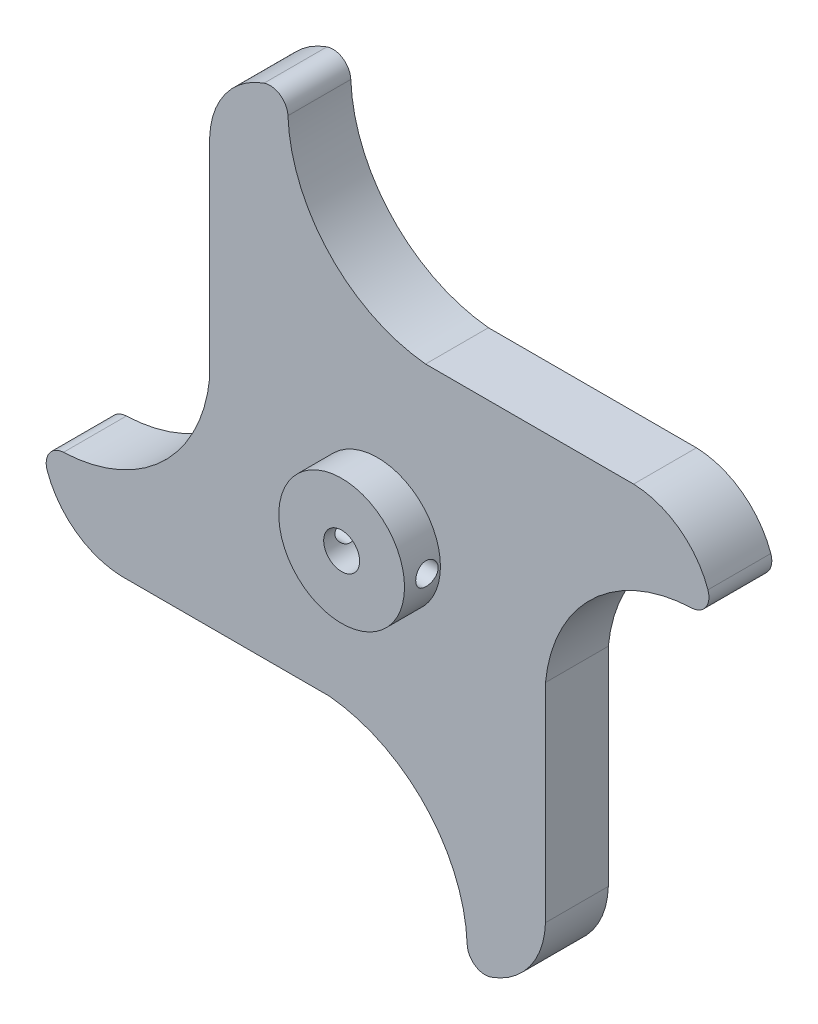
SolidWorks part; units mm, degrees
ref_plane "前视基准面" through (0, 0, 0) normal (0, 0, 1) x (1, 0, 0)
ref_plane "上视基准面" through (0, 0, 0) normal (0, 1, 0) x (1, 0, 0)
ref_plane "右视基准面" through (0, 0, 0) normal (1, 0, 0) x (0, 0, -1)
sketch "草图1" plane through (0, 0, 0) normal (0, 0, 1) x (1, 0, 0)
  circle A0 centre (0, 0) radius 2
  arc A5 (40.8798, 28.7896) -> (28.7896, 40.8798) centre (0, 0) ccw
  arc A7 (-28.7896, 40.8798) -> (-40.8798, 28.7896) centre (0, 0) ccw
  arc A9 (-40.8798, -28.7896) -> (-28.7896, -40.8798) centre (0, 0) ccw
  arc A11 (28.7896, -40.8798) -> (40.8798, -28.7896) centre (0, 0) ccw
  arc A13 (-22.8945, 32.8) -> (22.8945, 32.8) centre (0, 55.6945) ccw
  arc A14 (32.8, 22.8945) -> (32.8, -22.8945) centre (55.6945, 0) ccw
  arc A15 (22.8945, -32.8) -> (-22.8945, -32.8) centre (0, -55.6945) ccw
  arc A16 (-32.8, -22.8945) -> (-32.8, 22.8945) centre (-55.6945, 0) ccw
  arc A21 (-28.7896, 40.8798) -> (28.7896, 40.8798) centre (0, 55.6945) ccw
  arc A22 (40.8798, 28.7896) -> (40.8798, -28.7896) centre (55.6945, 0) ccw
  arc A23 (28.7896, -40.8798) -> (-28.7896, -40.8798) centre (0, -55.6945) ccw
  arc A24 (-40.8798, -28.7896) -> (-40.8798, 28.7896) centre (-55.6945, 0) ccw
  point P13 (45, 0)
  point P16 (0, 0)
  point P45 (0, 0)
  point P47 (0, 0)
  point P63 (0, 0)
  dimension "D1" = 4
  dimension "D3" = 4
  dimension "D4" = 4
extrude "凸台-拉伸1" add sketch "草图1" along normal blind 7 contours A24 A16 A9 A23 A15 A11 A22 A14 A5 A21 A13 A7 A0
sketch "草图2" plane through (0, 0, 7) normal (0, 0, 1) x (1, 0, 0)
  line L0 (24.2343, 0) -> (24.2343, 20.8516)
  line L1 (0, -24.2343) -> (-200, -24.2343)
  line L2 (-200, -71.6) -> (3.2733, -71.6)
  line L3 (0, -70) -> (-200, -70)
  line L4 (-200, -23.4) -> (-200, -71.6)
  line L5 (24.2343, 34.0432) -> (24.2343, 20.8516)
  line L6 (-200, -47.5) -> (-20.9464, -47.5)
  line L7 (-200, -23.4) -> (-42.5285, -23.4)
  line L8 (70, 0) -> (70, 107.3223)
  line L9 (24.2343, 34.0432) -> (24.2343, 107.3223)
  line L10 (-35.8334, -17.6395) -> (24.2343, 34.0432)
  line L11 (24.2343, 34.0432) -> (-43.4982, -24.2343)
  line L12 (0, -24.2343) -> (0, 0)
  line L13 (0, 0) -> (0, -24.2343)
  line L14 (-43.4982, -24.2343) -> (-43.4982, -70)
  line L15 (-310.8913, -229.5208) -> (-198.8913, -229.5208)
  line L16 (-254.8913, -229.5208) -> (-251.3913, -229.5208)
  line L17 (-251.3913, -229.5208) -> (-258.3913, -229.5208)
  line L18 (-258.3913, -229.5208) -> (-258.3913, -112.5315)
  line L19 (-258.3913, -112.5315) -> (-251.3913, -112.5315)
  line L20 (-251.3913, -112.5315) -> (-251.3913, -229.5208)
  line L21 (24.2343, 107.3223) -> (70, 107.3223)
  line L22 (47.1172, 107.3223) -> (47.1172, -141.393)
  line L23 (-20.9464, -47.5) -> (114.3656, -47.5)
  line L24 (0, 0) -> (0, -24.2343)
  circle A0 centre (0, -49) radius 21
  circle A1 centre (-310.8913, -229.5208) radius 38.25
  arc A2 (0, -24.2343) -> (24.2343, 0) centre (0, 0) ccw
  arc A3 (0, -70) -> (70, 0) centre (0, 0) ccw
  circle A4 centre (-198.8913, -229.5208) radius 38.25
  circle A5 centre (0, 0) radius 47.1172
  circle A10 centre (-254.8913, -208.9571) radius 21.4063
  point P19 (0, 0)
sketch "草图5" plane through (0, 0, 7) normal (0, 0, 1) x (1, 0, 0)
  line L1 (0, 2.5) -> (-1.7806, 2.5)
  line L2 (-1.7806, 2.5) -> (1.6583, 2.5)
  arc A0 (1.6583, 2.5) -> (-1.6583, 2.5) centre (0, 0) ccw
  circle A1 centre (0, 0) radius 7
extrude "凸台-拉伸2" add sketch "草图5" along normal blind 4
sketch "草图11" plane through (0, 0, 0) normal (1, 0, 0) x (0, 0, -1)
  line L0 (0, 0) -> (-7, 0)
  line L1 (-7, 0) -> (-10, 0)
  circle A0 centre (-8.5, 0) radius 1.25
extrude "切除-拉伸5" cut sketch "草图11" against normal blind 15 and the other way blind 8 contours L1 A0 | L1 A0
sketch "草图13" plane through (0, 0, 0) normal (0, 0, -1) x (-1, 0, 0)
  arc A0 (-25.2436, 31.0284) -> (25.2436, 31.0284) centre (0, 50.6945) ccw
  arc A1 (31.0284, 25.2436) -> (31.0284, -25.2436) centre (50.6945, 0) ccw
  arc A2 (25.2436, -31.0284) -> (-25.2436, -31.0284) centre (0, -50.6945) ccw
  arc A3 (-31.0284, -25.2436) -> (-31.0284, 25.2436) centre (-50.6945, 0) ccw
  arc A4 (-25.2436, 31.0284) -> (-31.0284, 25.2436) centre (0, 0) ccw
  circle A5 centre (0, 0) radius 82.6945
  arc A6 (-31.0284, -25.2436) -> (-25.2436, -31.0284) centre (0, 0) ccw
  arc A7 (25.2436, -31.0284) -> (31.0284, -25.2436) centre (0, 0) ccw
  arc A8 (31.0284, 25.2436) -> (25.2436, 31.0284) centre (0, 0) ccw
  point P14 (0, 0)
  dimension "D1" = 4
extrude "切除-拉伸13" cut sketch "草图13" against normal blind 10
fillet "圆角1" radius 2 4 edges at (-31.0284, -25.2436, 3.5) (31.0284, -25.2436, 3.5) (25.2436, 31.0284, 3.5) (-31.0284, 25.2436, 3.5)
fillet "圆角2" radius 2 4 edges at (-25.2436, -31.0284, 3.5) (25.2436, -31.0284, 3.5) (31.0284, 25.2436, 3.5) (-25.2436, 31.0284, 3.5)
sketch "草图14" plane through (0, 0, 0) normal (0, 0, -1) x (-1, 0, 0)
  line L0 (0, 18.6945) -> (-34.0956, 18.6945)
  line L1 (18.6945, 0) -> (18.6945, 34.0956)
  line L2 (0, -18.6945) -> (34.0956, -18.6945)
  line L3 (-18.6945, 0) -> (-18.6945, -34.0956)
  line L4 (34.0956, -16.9082) -> (34.0956, -18.6945)
  line L5 (-16.9082, -34.0956) -> (-18.6945, -34.0956)
  line L6 (-34.0956, 16.9082) -> (-34.0956, 18.6945)
  line L7 (16.9082, 34.0956) -> (18.6945, 34.0956)
  line L8 (13.8017, 34.0956) -> (18.6945, 34.0956)
  line L9 (34.0956, -13.8017) -> (34.0956, -18.6945)
  line L10 (-13.8017, -34.0956) -> (-18.6945, -34.0956)
  line L11 (-34.0956, 13.8017) -> (-34.0956, 18.6945)
  arc A1 (-23.9852, 29.5117) -> (23.9852, 29.5117) centre (0, 50.6945) ccw construction
  arc A5 (0, 18.6945) -> (13.8017, 34.0956) centre (-0.7997, 33.296) ccw
  arc A6 (18.6945, 0) -> (34.0956, -13.8017) centre (33.296, 0.7997) ccw
  arc A7 (0, -18.6945) -> (-13.8017, -34.0956) centre (0.7997, -33.296) ccw
  arc A8 (-18.6945, 0) -> (-34.0956, 13.8017) centre (-33.296, -0.7997) ccw
  point P22 (0, 0)
  point P29 (0, 0)
  point P35 (0, 0)
  point P41 (0, 0)
  dimension "D1" = 4
  dimension "D3" = 4
  dimension "D2" = 4
  dimension "D4" = 4
extrude "凸台-拉伸5" add sketch "草图14" against normal up to surface (7 mm away) up to face at (0, 0, 7)
sketch "草图15" plane through (0, 0, 0) normal (0, 0, -1) x (-1, 0, 0)
  line L0 (-24.7231, 18.6945) -> (0, 18.6945)
  line L1 (18.6945, 0) -> (18.6945, 24.7231)
  line L2 (24.7231, -18.6945) -> (0.9271, -18.708)
  line L3 (24.7231, -18.6945) -> (0, -18.6945)
  line L4 (18.6945, 24.7231) -> (18.6945, 0)
  line L5 (24.7231, -18.6945) -> (0, -18.6945)
  line L6 (-18.6945, -24.7231) -> (-18.6945, 0)
  line L7 (-18.6945, -24.7231) -> (-25.6921, -33.3347)
  line L8 (-25.6921, -33.3347) -> (-42.4976, -12.5302)
  line L9 (-42.4976, -12.5302) -> (-18.6945, 0)
  line L10 (-12.5302, 42.4976) -> (0, 18.6945)
  line L11 (-33.3347, 25.6921) -> (-12.5302, 42.4976)
  line L12 (-24.7231, 18.6945) -> (-33.3347, 25.6921)
  line L13 (42.4976, 12.5302) -> (18.6945, 0)
  line L14 (25.6921, 33.3347) -> (42.4976, 12.5302)
  line L15 (18.6945, 24.7231) -> (25.6921, 33.3347)
  line L16 (12.5302, -42.4976) -> (0, -18.6945)
  line L17 (33.3347, -25.6921) -> (12.5302, -42.4976)
  line L18 (24.7231, -18.6945) -> (33.3347, -25.6921)
  arc A0 (-23.9852, 29.5117) -> (0, 18.6945) centre (0, 50.6945) ccw construction
  arc A1 (0, 18.6945) -> (13.8017, 34.0956) centre (-0.7997, 33.296) ccw construction
  arc A2 (18.6945, 24.7231) -> (23.9852, 29.5117) centre (0, 50.6945) ccw construction
  arc A3 (23.9852, -29.5117) -> (0, -18.6945) centre (0, -50.6945) ccw construction
  point P35 (0, 0)
  point P47 (0, 0)
  arc M1 (-23.9852, -29.5117) -> (-18.6945, -24.7231) centre (0, -50.6945) cw
  arc M5 (0, -18.6945) -> (23.9852, -29.5117) centre (0, -50.6945) cw
  arc M6 (23.9852, -29.5117) -> (26.8255, -29.6714) centre (25.4843, -28.1878) ccw
  arc M7 (26.8255, -29.6714) -> (29.6714, -26.8255) centre (0, 0) ccw
  arc M8 (29.6714, -26.8255) -> (29.5117, -23.9852) centre (28.1878, -25.4843) ccw
  arc M9 (29.5117, -23.9852) -> (24.7231, -18.6945) centre (50.6945, 0) cw
  arc M13 (18.6945, 0) -> (29.5117, 23.9852) centre (50.6945, 0) cw
  arc M14 (29.5117, 23.9852) -> (29.6714, 26.8255) centre (28.1878, 25.4843) ccw
  arc M15 (29.6714, 26.8255) -> (26.8255, 29.6714) centre (0, 0) ccw
  arc M16 (26.8255, 29.6714) -> (23.9852, 29.5117) centre (25.4843, 28.1878) ccw
  arc M17 (23.9852, 29.5117) -> (18.6945, 24.7231) centre (0, 50.6945) cw
  arc M21 (0, 18.6945) -> (-23.9852, 29.5117) centre (0, 50.6945) cw
  arc M22 (-23.9852, 29.5117) -> (-26.8255, 29.6714) centre (-25.4843, 28.1878) ccw
  arc M23 (-26.8255, 29.6714) -> (-29.6714, 26.8255) centre (0, 0) ccw
  arc M24 (-29.6714, 26.8255) -> (-29.5117, 23.9852) centre (-28.1878, 25.4843) ccw
  arc M25 (-29.5117, 23.9852) -> (-24.7231, 18.6945) centre (-50.6945, 0) cw
  arc M29 (-18.6945, 0) -> (-29.5117, -23.9852) centre (-50.6945, 0) cw
  arc M30 (-29.5117, -23.9852) -> (-29.6714, -26.8255) centre (-28.1878, -25.4843) ccw
  arc M31 (-29.6714, -26.8255) -> (-26.8255, -29.6714) centre (0, 0) ccw
  arc M32 (-26.8255, -29.6714) -> (-23.9852, -29.5117) centre (-25.4843, -28.1878) ccw
  dimension "D1" = 4
  dimension "D2" = 4
extrude "切除-拉伸14" cut sketch "草图15" against normal blind 10 contours L12 L10 L11 M25 M24 M23 M22 M21 | L0 M25 M21 M22 M23 M24 | L1 M13 M14 M15 M16 M17 | L15 L13 L14 M17 M16 M15 M14 M13 | L2 M9 M5 M6 M7 M8 | L18 L16 L17 M9 M8 M7 M6 M5 | L9 L8 L7 M1 M32 M31 M30 M29 | L6 M1 M29 M30 M31 M32
fillet "圆角3" radius 3 4 edges at (34.0956, 18.6945, 3.5) (18.6945, -34.0956, 3.5) (-34.0956, -18.6945, 3.5) (-18.6945, 34.0956, 3.5)
fillet "圆角4" radius 1 4 edges at (-34.0956, -13.8017, 3.5) (13.8017, -34.0956, 3.5) (34.0956, 13.8017, 3.5) (-13.8017, 34.0956, 3.5)
sketch "草图16" plane through (0, 0, 0) normal (0, 0, -1) x (-1, 0, 0)
  arc A0 (5.3467, -18.6945) -> (-9.9109, -37.2905) centre (7.0159, -35.6213) ccw
  arc A1 (-18.6945, -27.9842) -> (-9.9109, -37.2905) centre (-9.6496, -28.2455) ccw
  arc A2 (-18.6945, -5.3467) -> (-37.2905, 9.9109) centre (-35.6213, -7.0159) ccw
  arc A3 (-27.9842, 18.6945) -> (-37.2905, 9.9109) centre (-28.2455, 9.6496) ccw
  arc A4 (-5.3467, 18.6945) -> (9.9109, 37.2905) centre (-7.0159, 35.6213) ccw
  arc A5 (27.9842, -18.6945) -> (37.2905, -9.9109) centre (28.2455, -9.6496) ccw
  arc A6 (18.6945, 27.9842) -> (9.9109, 37.2905) centre (9.6496, 28.2455) ccw
  arc A9 (18.6945, 5.3467) -> (37.2905, -9.9109) centre (35.6213, 7.0159) ccw
  point P21 (0, 0)
  line M3 (34.0956, -15.6945) -> (34.0956, -14.8223)
  arc M4 (34.0956, -14.8223) -> (33.1085, -13.8224) centre (33.0956, -14.8223) ccw
  arc M5 (33.1085, -13.8224) -> (18.6945, 0) centre (33.296, 0.7997) cw
  line M6 (18.6945, 0) -> (18.6945, 31.0956)
  arc M7 (18.6945, 31.0956) -> (15.6945, 34.0956) centre (15.6945, 31.0956) ccw
  line M8 (15.6945, 34.0956) -> (14.8223, 34.0956)
  arc M9 (14.8223, 34.0956) -> (13.8224, 33.1085) centre (14.8223, 33.0956) ccw
  arc M10 (13.8224, 33.1085) -> (0, 18.6945) centre (-0.7997, 33.296) cw
  line M11 (0, 18.6945) -> (-31.0956, 18.6945)
  arc M12 (-31.0956, 18.6945) -> (-34.0956, 15.6945) centre (-31.0956, 15.6945) ccw
  line M13 (-34.0956, 15.6945) -> (-34.0956, 14.8223)
  arc M14 (-34.0956, 14.8223) -> (-33.1085, 13.8224) centre (-33.0956, 14.8223) ccw
  arc M15 (-33.1085, 13.8224) -> (-18.6945, 0) centre (-33.296, -0.7997) cw
  line M16 (-18.6945, 0) -> (-18.6945, -31.0956)
  arc M17 (-18.6945, -31.0956) -> (-15.6945, -34.0956) centre (-15.6945, -31.0956) ccw
  line M18 (-15.6945, -34.0956) -> (-14.8223, -34.0956)
  arc M19 (-14.8223, -34.0956) -> (-13.8224, -33.1085) centre (-14.8223, -33.0956) ccw
  arc M20 (-13.8224, -33.1085) -> (0, -18.6945) centre (0.7997, -33.296) cw
  arc M21 (0, -18.6945) -> (0.9271, -18.708) centre (0, -50.6945) cw
  line M22 (0.9271, -18.708) -> (24.7231, -18.6945)
  arc M24 (31.0956, -18.6945) -> (34.0956, -15.6945) centre (31.0956, -15.6945) ccw
  dimension "D1" = 4
sketch "草图17" plane through (0, 0, 7) normal (0, 0, 1) x (1, 0, 0)
  arc A0 (-18.6945, 27.9842) -> (-9.9109, 37.2905) centre (-9.6496, 28.2455) cw
  arc A1 (-9.9109, 37.2905) -> (5.3467, 18.6945) centre (7.0159, 35.6213) ccw
  arc A2 (37.2905, 9.9109) -> (18.6945, -5.3467) centre (35.6213, -7.0159) ccw
  arc A3 (27.9842, 18.6945) -> (37.2905, 9.9109) centre (28.2455, 9.6496) cw
  arc A4 (9.9109, -37.2905) -> (-5.3467, -18.6945) centre (-7.0159, -35.6213) ccw
  arc A5 (18.6945, -27.9842) -> (9.9109, -37.2905) centre (9.6496, -28.2455) cw
  arc A6 (-37.2905, -9.9109) -> (-18.6945, 5.3467) centre (-35.6213, 7.0159) ccw
  arc A7 (-27.9842, -18.6945) -> (-37.2905, -9.9109) centre (-28.2455, -9.6496) cw
  point P26 (0, 0)
  dimension "D1" = 4
extrude "凸台-拉伸6" add sketch "草图16" against normal up to surface (7 mm away) contours A6 A4 M7 M11 M10 M9 M8 | A3 A2 M12 M16 M15 M14 M13 | A1 A0 M17 M22 M21 M20 M19 M18 | A9 A5 M6 M5 M4 M3 M24 up to face at (-1.1659, -1.7, 7)
sketch "草图18" plane through (0, 0, 7) normal (0, 0, 1) x (1, 0, 0)
  line L0 (5.3467, 18.6945) -> (27.9842, 18.6945)
  line L1 (18.6945, -5.3467) -> (18.6945, -27.9842)
  line L2 (-5.3467, -18.6945) -> (-27.9842, -18.6945)
  line L3 (-18.6945, 5.3467) -> (-18.6945, 27.9842)
  arc A0 (-18.6945, 27.9842) -> (-9.9109, 37.2905) centre (-9.6496, 28.2455) cw
  arc A1 (-9.9109, 37.2905) -> (5.3467, 18.6945) centre (7.0159, 35.6213) ccw
  arc A2 (27.9842, 18.6945) -> (37.2905, 9.9109) centre (28.2455, 9.6496) cw
  arc A3 (37.2905, 9.9109) -> (18.6945, -5.3467) centre (35.6213, -7.0159) ccw
  arc A4 (18.6945, -27.9842) -> (9.9109, -37.2905) centre (9.6496, -28.2455) cw
  arc A5 (9.9109, -37.2905) -> (-5.3467, -18.6945) centre (-7.0159, -35.6213) ccw
  arc A6 (-27.9842, -18.6945) -> (-37.2905, -9.9109) centre (-28.2455, -9.6496) cw
  arc A7 (-37.2905, -9.9109) -> (-18.6945, 5.3467) centre (-35.6213, 7.0159) ccw
  circle A8 centre (0, 0) radius 47.2388
  point P31 (0, 0)
  dimension "D1" = 4
extrude "切除-拉伸15" cut sketch "草图18" against normal blind 10
fillet "圆角5" radius 2 4 edges at (-37.2905, -9.9109, 3.5) (9.9109, -37.2905, 3.5) (37.2905, 9.9109, 3.5) (-9.9109, 37.2905, 3.5)
sketch "草图19" plane through (0, 0, 7) normal (0, 0, 1) x (1, 0, 0)
  circle A0 centre (0, 0) radius 9.5
  circle A1 centre (9.5, 0) radius 3
extrude "切除-拉伸16" [suppressed] cut sketch "草图19" against normal blind 10 contours A0 A1 | A0 A1
ref_plane "基准面1" through (0, 0, 3.5) normal (0, 0, -1) x (-1, 0, 0)
